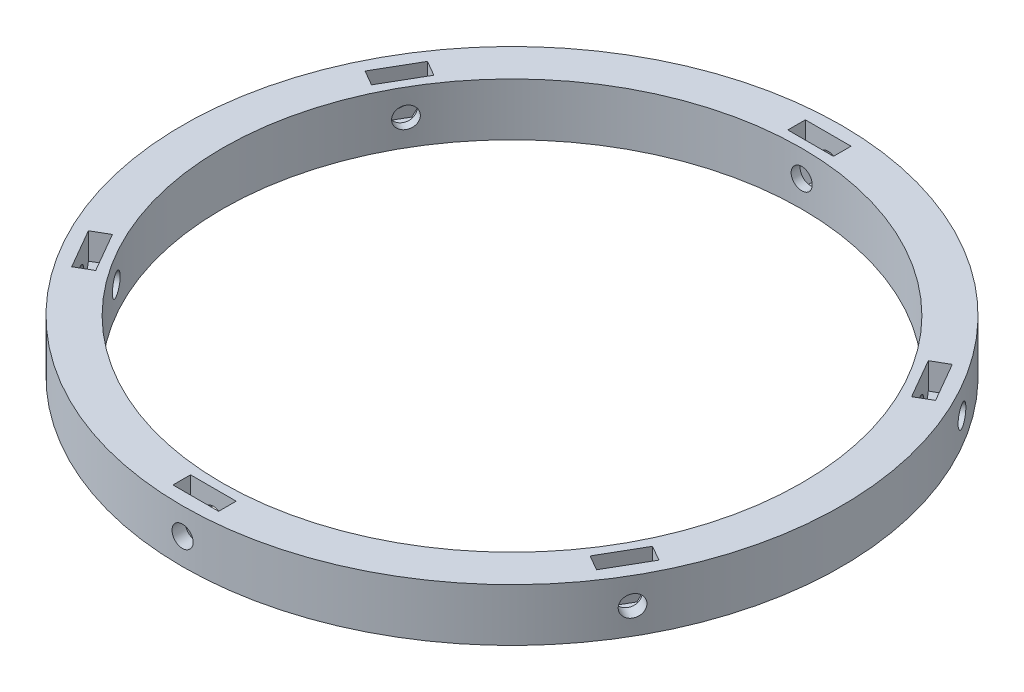
SolidWorks part; units mm, degrees
ref_plane "Front Plane" through (0, 0, 0) normal (0, 0, 1) x (1, 0, 0)
ref_plane "Top Plane" through (0, 0, 0) normal (0, 1, 0) x (1, 0, 0)
ref_plane "Right Plane" through (0, 0, 0) normal (1, 0, 0) x (0, 0, -1)
sketch "Sketch2" plane through (0, 0, 0) normal (0, 1, 0) x (1, 0, 0)
  circle A0 centre (0, 0) radius 47.6504
  circle A1 centre (0, 0) radius 41.91
  dimension "D1" = 95.3008
  dimension "D2" = 83.82
extrude "Boss-Extrude1" add sketch "Sketch2" along normal blind 7.62
ref_plane "Plane1" through (0, 0, 44.45) normal (0, 0, 1) x (1, 0, 0)
sketch "Sketch4" plane through (0, 0, 44.45) normal (0, 0, 1) x (1, 0, 0)
  line L0 (0, 0) -> (0, 7.62)
  line L1 (41.91, 7.62) -> (-41.91, 7.62) construction
  line L2 (3.302, 3.81) -> (3.302, 7.62)
  line L3 (3.302, 3.81) -> (1.651, 6.6696)
  line L4 (1.651, 6.6696) -> (-1.651, 6.6696)
  line L5 (-1.651, 6.6696) -> (-3.302, 3.81)
  line L6 (-3.302, 3.81) -> (-1.651, 0.9504)
  line L7 (-1.651, 0.9504) -> (1.651, 0.9504)
  line L8 (1.651, 0.9504) -> (3.302, 3.81)
  line L9 (47.6504, 7.62) -> (-47.6504, 7.62) construction
  line L10 (3.302, 7.62) -> (-3.302, 7.62)
  line L11 (-3.302, 7.62) -> (-3.302, 3.81)
  circle A0 centre (0, 3.81) radius 2.8596 construction
  dimension "D1" = 3.302
extrude "Cut-Extrude1" cut sketch "Sketch4" against normal mid plane 2.54 contours L6 L7 L0 L4 L5 | L7 L8 L3 L4 L0 | L2 L10 L0 L4 L3 | L10 L11 L5 L4 L0
sketch "Sketch6" plane through (0, 0, 44.45) normal (0, 0, 1) x (1, 0, 0)
  line L0 (0, 0) -> (0, 7.62) construction
  line L1 (3.302, 7.62) -> (-3.302, 7.62) construction
  circle A0 centre (0, 3.81) radius 1.524
  dimension "D1" = 3.048
extrude "Cut-Extrude2" cut sketch "Sketch6" against normal mid plane 12.446
pattern_circular "CirPattern1" count 6 over 360 about axis through (0, 0, 0) along (0, 1, 0) of "Cut-Extrude2", "Cut-Extrude1"
